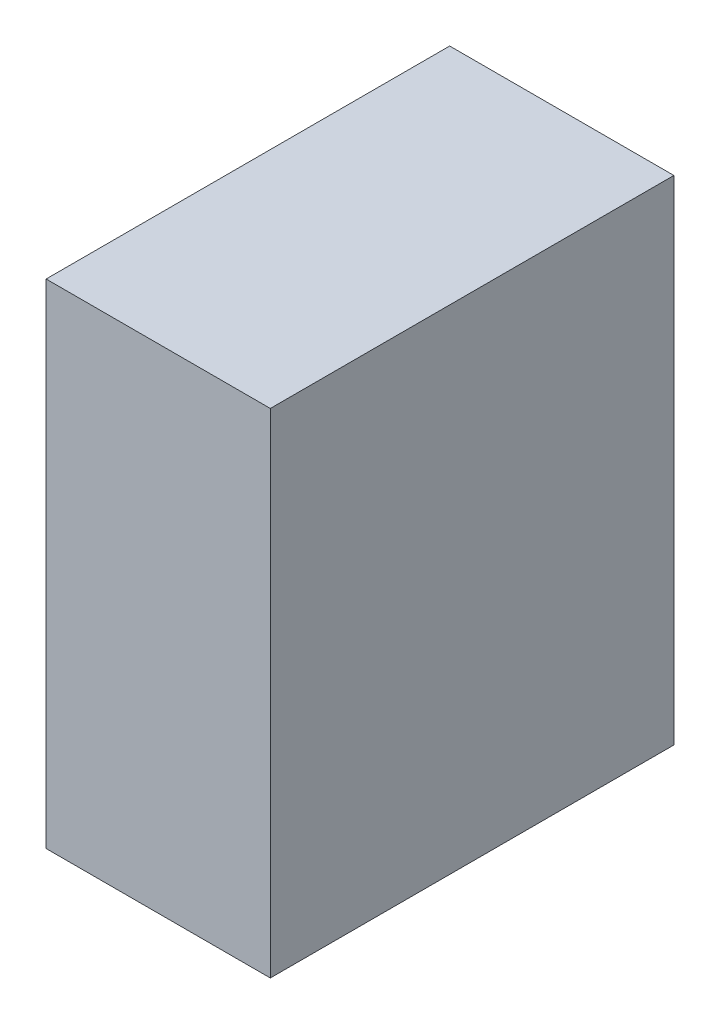
SolidWorks part; units mm, degrees
ref_plane "Front Plane" through (0, 0, 0) normal (0, 0, 1) x (1, 0, 0)
ref_plane "Top Plane" through (0, 0, 0) normal (0, 1, 0) x (1, 0, 0)
ref_plane "Right Plane" through (0, 0, 0) normal (1, 0, 0) x (0, 0, -1)
sketch "Sketch1" plane through (0, 0, 0) normal (1, 0, 0) x (0, 0, -1)
  line L1 (0, 0) -> (90, 0)
  line L2 (0, 0) -> (0, 110)
  line L3 (0, 110) -> (90, 110)
  line L4 (90, 0) -> (90, 110)
  dimension "D1" = 90
  dimension "D2" = 110
extrude "Boss-Extrude1" add sketch "Sketch1" along normal mid plane 50
